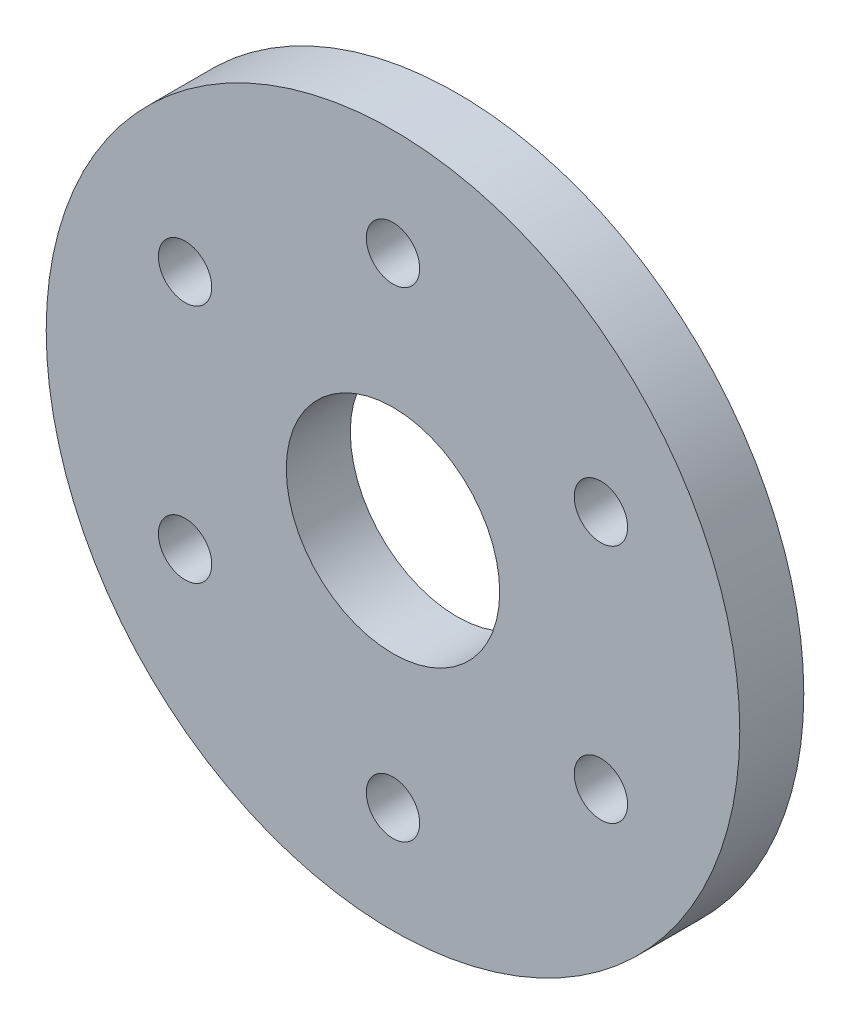
SolidWorks part; units mm, degrees
material "ABS"
ref_plane "前视基准面" through (0, 0, 0) normal (0, 0, 1) x (1, 0, 0)
ref_plane "上视基准面" through (0, 0, 0) normal (0, 1, 0) x (1, 0, 0)
ref_plane "右视基准面" through (0, 0, 0) normal (1, 0, 0) x (0, 0, -1)
other "Configuration Table"
sketch "草图1" plane through (0, 0, 0) normal (0, 0, 1) x (1, 0, 0)
  circle A0 centre (0, 0) radius 10
  circle A1 centre (0, 0) radius 32.5
  dimension "D1" = 20
  dimension "D2" = 65
extrude "凸台-拉伸1" add sketch "草图1" along normal blind 6
sketch "草图2" plane through (0, 0, 6) normal (0, 0, 1) x (1, 0, 0)
  circle A0 centre (0, 0) radius 22.5 construction
  circle A1 centre (0, 22.5) radius 2.5
  circle A2 centre (19.4856, 11.25) radius 2.5
  circle A3 centre (19.4856, -11.25) radius 2.5
  circle A4 centre (0, -22.5) radius 2.5
  circle A5 centre (-19.4856, -11.25) radius 2.5
  circle A6 centre (-19.4856, 11.25) radius 2.5
  point P6 (-23.2353, 10.8463)
  point P7 (0, 0)
  point P17 (0, 0)
  dimension "D1" = 45
  dimension "D2" = 5
  dimension "D3" = 6
extrude "切除-拉伸1" cut sketch "草图2" against normal blind 6
